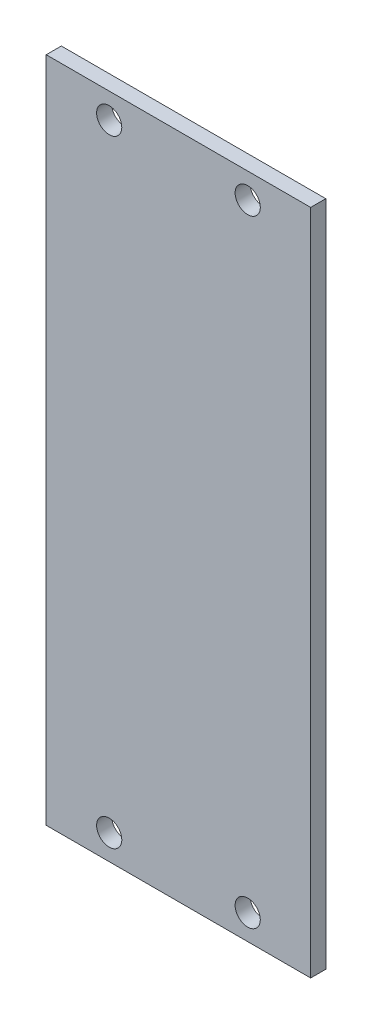
SolidWorks part; units mm, degrees
ref_plane "前视基准面" through (0, 0, 0) normal (0, 0, 1) x (1, 0, 0)
ref_plane "上视基准面" through (0, 0, 0) normal (0, 1, 0) x (1, 0, 0)
ref_plane "右视基准面" through (0, 0, 0) normal (1, 0, 0) x (0, 0, -1)
sketch "草图1" plane through (0, 0, 0) normal (0, 0, 1) x (1, 0, 0)
  line L0 (-1000, 0) -> (49000, 0) construction
  line L1 (10.5, -26.5) -> (-10.5, -26.5)
  line L2 (10.5, -26.5) -> (10.5, 26.5)
  line L3 (10.5, 26.5) -> (-10.5, 26.5)
  line L4 (-10.5, -26.5) -> (-10.5, 26.5)
  line L5 (10.5, -26.5) -> (-10.5, 26.5) construction
  line L6 (10.5, 26.5) -> (-10.5, -26.5) construction
  line L7 (0, -1000) -> (0, 49000) construction
  circle A0 centre (-5.5, 24.5) radius 1
  circle A2 centre (5.5, 24.5) radius 1
  circle A3 centre (5.5, -24.5) radius 1
  circle A4 centre (-5.5, -24.5) radius 1
  point P0 (0, 0)
  dimension "D4" = 2
  dimension "D5" = 2
  dimension "D1" = 21
  dimension "D2" = 53
  dimension "D3" = 5
extrude "凸台-拉伸1" add sketch "草图1" along normal blind 1.2
